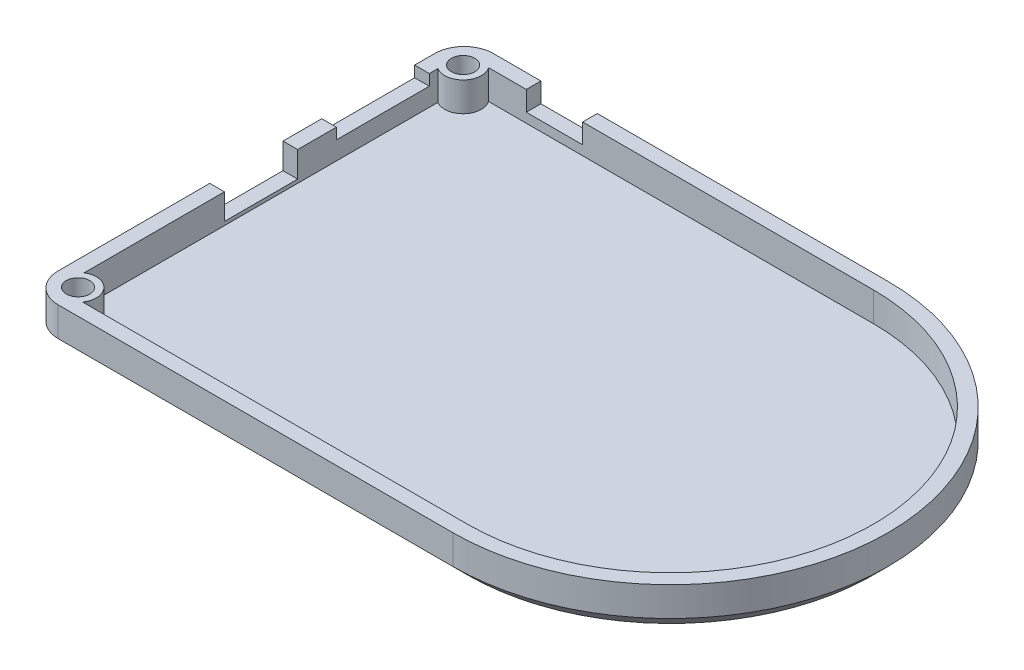
SolidWorks part; units mm, degrees
ref_plane "前视基准面" through (0, 0, 0) normal (0, 0, 1) x (1, 0, 0)
ref_plane "上视基准面" through (0, 0, 0) normal (0, 1, 0) x (1, 0, 0)
ref_plane "右视基准面" through (0, 0, 0) normal (1, 0, 0) x (0, 0, -1)
other "Configuration Table"
sketch "草图1" plane through (0, 0, 0) normal (0, 1, 0) x (1, 0, 0)
  line L1 (-24.955, -29.72) -> (28.955, -29.72)
  line L2 (-28.955, -25.72) -> (-28.955, 25.72)
  line L3 (-24.955, 29.72) -> (28.955, 29.72)
  line L5 (-28.955, -29.72) -> (28.955, 29.72) construction
  line L6 (-28.955, 29.72) -> (28.955, -29.72) construction
  arc A0 (28.955, 29.72) -> (28.955, -29.72) centre (28.955, 0) cw
  arc A1 (-24.955, -29.72) -> (-28.955, -25.72) centre (-24.955, -25.72) cw
  arc A2 (-28.955, 25.72) -> (-24.955, 29.72) centre (-24.955, 25.72) cw
  point P0 (0, 0)
  dimension "D3" = 29.72
  dimension "D5" = 4
  dimension "D1" = 59.44
  dimension "D2" = 57.91
  dimension "D4" = 57.91
extrude "凸台-拉伸1" add sketch "草图1" along normal blind 2
sketch "草图2" plane through (0, 2, 0) normal (0, 1, 0) x (1, 0, 0)
  line L0 (-26.955, 24.1546) -> (-26.955, -24.1546)
  line L1 (-23.6044, -27.72) -> (28.955, -27.72)
  line L2 (28.955, 27.72) -> (-23.6044, 27.72)
  line L3 (28.955, 29.72) -> (-24.955, 29.72)
  line L4 (-28.955, 25.72) -> (-28.955, -25.72)
  line L5 (-24.955, -29.72) -> (28.955, -29.72)
  line L6 (28.955, 29.72) -> (-24.955, 29.72)
  line L7 (-28.955, 25.72) -> (-28.955, -25.72)
  line L8 (-24.955, -29.72) -> (28.955, -29.72)
  line L9 (0, 0) -> (-46.3188, 0) construction
  line L10 (-26.955, 25.72) -> (-26.955, -25.72) construction
  line L11 (28.955, 27.72) -> (-24.955, 27.72) construction
  line L12 (-24.955, -27.72) -> (28.955, -27.72) construction
  arc A1 (28.955, -27.72) -> (28.955, 27.72) centre (28.955, 0) ccw
  arc A3 (28.955, -29.72) -> (28.955, 29.72) centre (28.955, 0) ccw
  arc A4 (-24.955, 29.72) -> (-28.955, 25.72) centre (-24.955, 25.72) ccw
  arc A5 (-28.955, -25.72) -> (-24.955, -29.72) centre (-24.955, -25.72) ccw
  arc A6 (28.955, -29.72) -> (28.955, 29.72) centre (28.955, 0) ccw
  arc A7 (-24.955, 29.72) -> (-28.955, 25.72) centre (-24.955, 25.72) ccw
  arc A8 (-28.955, -25.72) -> (-24.955, -29.72) centre (-24.955, -25.72) ccw
  arc A9 (-26.955, 24.1546) -> (-23.6044, 27.72) centre (-25.655, 26.29) ccw
  arc A10 (-26.955, -24.1546) -> (-23.6044, -27.72) centre (-25.655, -26.29) cw
  arc A11 (-24.955, 27.72) -> (-26.955, 25.72) centre (-24.955, 25.72) ccw construction
  arc A12 (-26.955, -25.72) -> (-24.955, -27.72) centre (-24.955, -25.72) ccw construction
  dimension "D3" = 3.3
  dimension "D5" = 5
  dimension "D4" = 3.43
  dimension "D1" = 0
  dimension "D2" = 2
extrude "凸台-拉伸2" add sketch "草图2" along normal blind 4
sketch "草图3" plane through (0, 6, 0) normal (0, 1, 0) x (1, 0, 0)
  line L0 (28.955, 29.72) -> (-24.955, 29.72) construction
  line L1 (-18.455, 29.72) -> (-10.755, 29.72)
  line L2 (-18.455, 29.72) -> (-18.455, 27.72)
  line L3 (-18.455, 27.72) -> (-10.755, 27.72)
  line L4 (-10.755, 29.72) -> (-10.755, 27.72)
  line L5 (-14.605, 27.72) -> (-14.605, 29.72) construction
  line L6 (-18.455, 28.72) -> (-10.755, 28.72) construction
  line L7 (28.955, 27.72) -> (-23.6044, 27.72) construction
  line L8 (-28.955, 25.72) -> (-28.955, -25.72) construction
  line L9 (-26.955, 24.1546) -> (-26.955, -24.1546) construction
  line L10 (-30.955, 5) -> (-26.955, 5)
  line L11 (-30.955, 5) -> (-30.955, -5)
  line L12 (-30.955, -5) -> (-26.955, -5)
  line L13 (-26.955, 5) -> (-26.955, -5)
  line L14 (-30.955, 5) -> (-26.955, -5) construction
  line L15 (-30.955, -5) -> (-26.955, 5) construction
  circle A0 centre (-25.655, 26.29) radius 1.6
  circle A1 centre (-25.655, -26.29) radius 1.6
  point P0 (-25.655, 26.29)
  point P1 (-25.655, -26.29)
  point P20 (-28.955, 0)
  point P68 (-14.605, 28.72)
  dimension "D1" = 3.2
  dimension "D2" = 3.2
  dimension "D3" = 10.5
  dimension "D4" = 18.2
  dimension "D5" = 10
extrude "切除-拉伸1" cut sketch "草图3" against normal blind 2.7
sketch "草图4" plane through (0, 6, 0) normal (0, 1, 0) x (1, 0, 0)
  circle A1 centre (-25.655, 26.29) radius 1.6
  circle A2 centre (-25.655, 26.29) radius 1.6
  circle A3 centre (-25.655, -26.29) radius 1.6
  circle A4 centre (-25.655, -26.29) radius 1.6
  dimension "D1" = 0
  dimension "D2" = 0
extrude "切除-拉伸2" cut sketch "草图4" against normal blind 5
chamfer "倒角1" distance 2 angle 45 6 edges at (-27.7834, 0, -28.5484) (-28.955, 0, 0) (2, 0, -29.72) (-27.7834, 0, 28.5484) (58.675, 0, 0) (2, 0, 29.72)
sketch "草图5" plane through (0, 6, 0) normal (0, 1, 0) x (1, 0, 0)
  line L0 (-28.955, 25.72) -> (-28.955, 5) construction
  line L1 (-28.955, 22.98) -> (-26.955, 22.98)
  line L2 (-28.955, 22.98) -> (-28.955, 10.29)
  line L3 (-28.955, 10.29) -> (-26.955, 10.29)
  line L4 (-26.955, 22.98) -> (-26.955, 10.29)
  line L5 (-27.955, 10.29) -> (-27.955, 22.98) construction
  line L6 (-28.955, 16.635) -> (-26.955, 16.635) construction
  line L7 (-26.955, 24.1546) -> (-26.955, 5) construction
  line L8 (28.955, 29.72) -> (-10.755, 29.72) construction
  point P64 (-27.955, 16.635)
  dimension "D1" = 6.74
  dimension "D2" = 19.43
extrude "切除-拉伸3" cut sketch "草图5" against normal blind 1.5
sketch "草图6" plane through (0, 3.3, 0) normal (0, 1, 0) x (1, 0, 0)
  line L4 (-28.955, 5) -> (-28.955, -5)
  line L5 (-28.955, -5) -> (-26.955, -5)
  line L6 (-26.955, -5) -> (-26.955, 5)
  line L7 (-26.955, 5) -> (-28.955, 5)
  line L8 (-28.955, 5) -> (-28.955, -5)
  line L9 (-28.955, -5) -> (-26.955, -5)
  line L10 (-26.955, -5) -> (-26.955, 5)
  line L11 (-26.955, 5) -> (-28.955, 5)
  dimension "D1" = 0
extrude "切除-拉伸4" cut sketch "草图6" against normal blind 0.8
